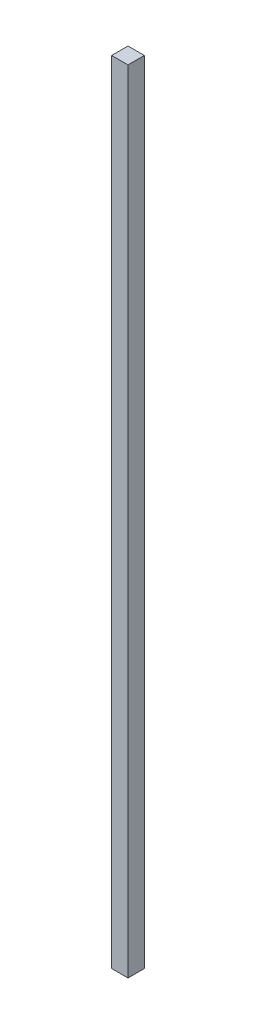
SolidWorks part; units mm, degrees
material "Alloy Steel"
ref_plane "Front Plane" through (0, 0, 0) normal (1, 0, 0) x (0, 1, 0)
ref_plane "Top Plane" through (0, 0, 0) normal (0, 0, 1) x (0, 1, 0)
ref_plane "Right Plane" through (0, 0, 0) normal (0, 1, 0) x (-1, 0, 0)
sketch "Sketch2" plane through (0, 0, 0) normal (1, 0, 0) x (0, 1, 0)
  line L0 (0, 0) -> (10000, 0)
  dimension "D1" = 10000
other "Hw5 SMALLBEAM207(1)"
ref_plane "Plane1" through (0, 0, 0) normal (0, 1, 0) x (0, 0, 1)
sketch "Sketch12" plane through (0, 0, 0) normal (0, 1, 0) x (0, 0, 1)
  line L0 (0, 103.5) -> (0, -103.5) construction
  line L1 (-103.5, -103.5) -> (103.5, -103.5)
  line L2 (-103.5, -103.5) -> (-103.5, 103.5)
  line L3 (-103.5, 103.5) -> (103.5, 103.5)
  line L4 (103.5, -103.5) -> (103.5, 103.5)
  point P6 (0, 0)
  point P7 (0, 0)
  dimension "D1" = 207
